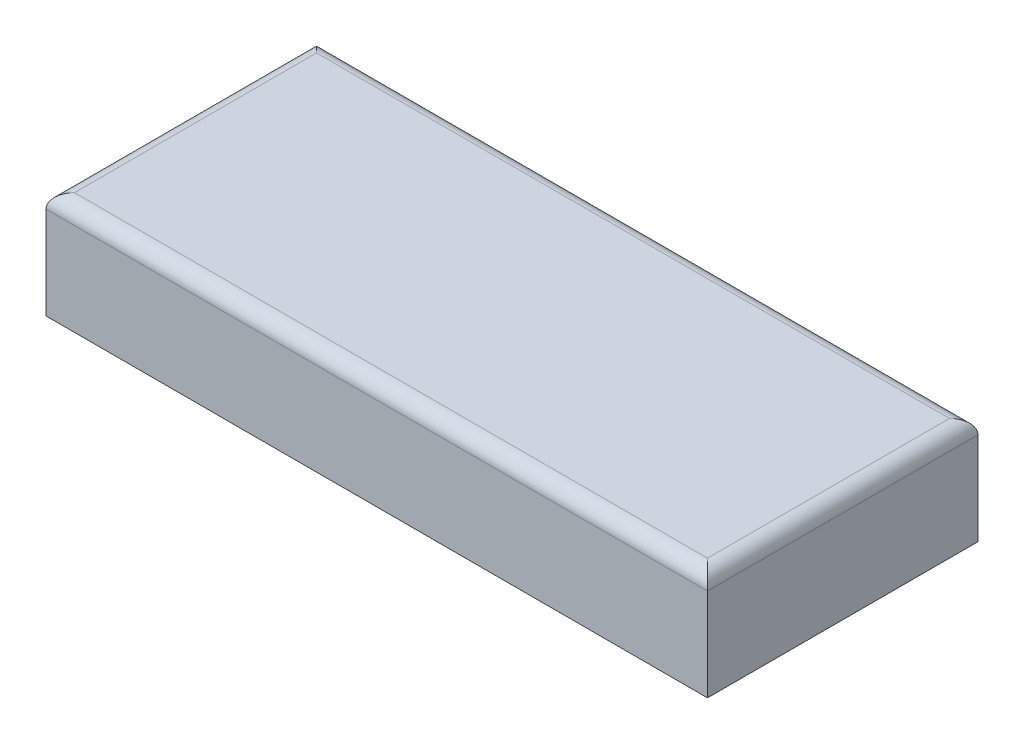
SolidWorks part; units mm, degrees
ref_plane "Front Plane" through (0, 0, 0) normal (0, 0, 1) x (1, 0, 0)
ref_plane "Top Plane" through (0, 0, 0) normal (0, 1, 0) x (1, 0, 0)
ref_plane "Right Plane" through (0, 0, 0) normal (1, 0, 0) x (0, 0, -1)
sketch "Sketch2" plane through (0, 0, 0) normal (0, 0, 1) x (1, 0, 0)
  line L0 (118.0235, 25.4) -> (0, 6.35) construction
  line L1 (0, 6.35) -> (118.0235, 6.35)
  line L2 (0, 6.35) -> (0, 25.4)
  line L3 (0, 25.4) -> (118.0235, 25.4)
  line L4 (118.0235, 25.4) -> (118.0235, 6.35)
  line L5 (0, 25.4) -> (118.0235, 6.35) construction
  line L6 (59.0117, 41.4555) -> (59.0117, -23.9342) construction
  line L7 (128.3518, 6.35) -> (-16.0436, 6.35) construction
  line L12 (0, 25.4) -> (0, 6.35)
extrude "Boss-Extrude1" add sketch "Sketch2" along normal blind 48.26 contours L2 L3 L4 L1
sketch "Sketch24" plane through (0, 6.35, 0) normal (0, -1, 0) x (-1, 0, 0)
  line L1 (-1.8766, -45.5651) -> (-116.1766, -45.5651)
  line L2 (-1.8766, -45.5651) -> (-1.8766, -2.3851)
  line L3 (-1.8766, -2.3851) -> (-116.1766, -2.3851)
  line L4 (-116.1766, -45.5651) -> (-116.1766, -2.3851)
extrude "Cut-Extrude2" cut sketch "Sketch24" against normal blind 17.78
sketch "Sketch25" plane through (0, 0, 0) normal (-1, 0, 0) x (0, 0, 1)
  line L1 (17.7551, 19.0381) -> (30.4551, 19.0381)
  line L2 (17.7551, 19.0381) -> (17.7551, 12.6881)
  line L3 (17.7551, 12.6881) -> (30.4551, 12.6881)
  line L4 (30.4551, 19.0381) -> (30.4551, 12.6881)
extrude "Cut-Extrude3" cut sketch "Sketch25" against normal blind 6.604
fillet "Fillet1" radius 2.54 4 edges at (118.0235, 25.4, 24.13) (59.0117, 25.4, 48.26) (0, 25.4, 24.13) (59.0117, 25.4, 0)
